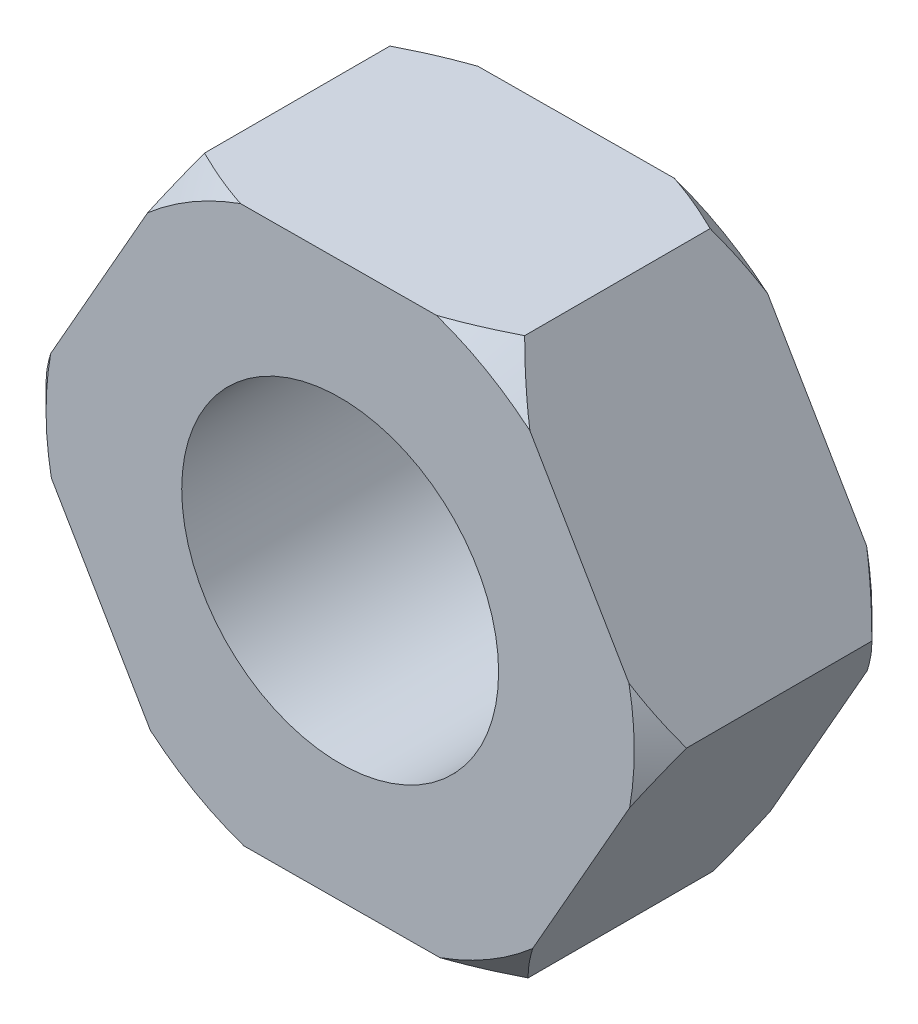
SolidWorks part; units mm, degrees
material "1023 Carbon Steel Sheet (SS)"
ref_plane "Front Plane" through (0, 0, 0) normal (0, 0, 1) x (1, 0, 0)
ref_plane "Top Plane" through (0, 0, 0) normal (0, 1, 0) x (1, 0, 0)
ref_plane "Right Plane" through (0, 0, 0) normal (1, 0, 0) x (0, 0, -1)
sketch "Sketch1" plane through (0, 0, 0) normal (0, 0, 1) x (1, 0, 0)
  line L1 (9.9953, 17.5621) -> (-10.2116, 17.4372)
  line L2 (-10.2116, 17.4372) -> (-20.2069, -0.1249)
  line L3 (-20.2069, -0.1249) -> (-9.9953, -17.5621)
  line L4 (-9.9953, -17.5621) -> (10.2116, -17.4372)
  line L5 (10.2116, -17.4372) -> (20.2069, 0.1249)
  line L6 (20.2069, 0.1249) -> (9.9953, 17.5621)
  circle A0 centre (0, 0) radius 17.5 construction
  circle A1 centre (0, 0) radius 10
  dimension "D2" = 20
  dimension "D1" = 35
extrude "Boss-Extrude1" add sketch "Sketch1" along normal blind 15
sketch "Sketch2" plane through (0, 0, 0) normal (0, 1, 0) x (1, 0, 0)
  line L0 (-23.2413, -7.5) -> (21.46, -7.5) construction
  line L1 (20.2069, 0) -> (9.9953, 0) construction
  line L2 (20.2069, -15) -> (9.9953, -15) construction
  line L3 (17.5607, 1) -> (21.2069, -2.6462)
  line L4 (21.2069, -2.6462) -> (21.2069, 1)
  line L5 (21.2069, 1) -> (17.5607, 1)
  line L6 (20.2069, -15) -> (20.2069, 0) construction
  line L7 (21.2069, -16) -> (17.5607, -16)
  line L8 (21.2069, -12.3538) -> (21.2069, -16)
  line L9 (17.5607, -16) -> (21.2069, -12.3538)
  line L10 (0, 0) -> (0, 7.2862) construction
  dimension "D1" = 1
  dimension "D2" = 1
revolve "Cut-Revolve1" cut sketch "Sketch2" angle 360 about L10
